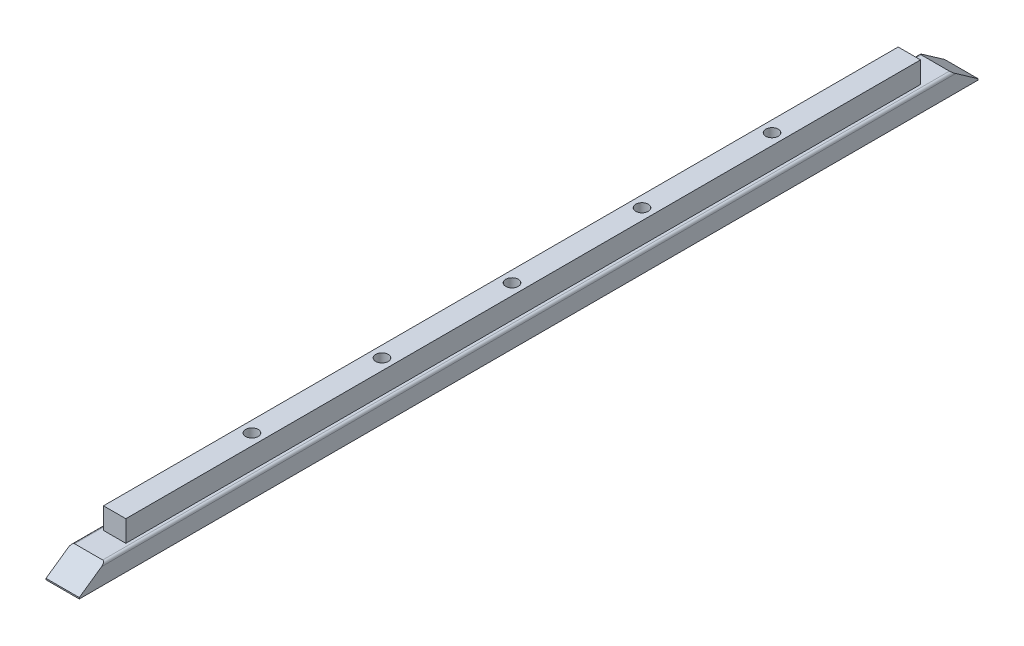
SolidWorks part; units mm, degrees
ref_plane "Front Plane" through (0, 0, 0) normal (0, 0, 1) x (1, 0, 0)
ref_plane "Top Plane" through (0, 0, 0) normal (0, 1, 0) x (1, 0, 0)
ref_plane "Right Plane" through (0, 0, 0) normal (1, 0, 0) x (0, 0, -1)
sketch "Sketch1" plane through (0, 0, 0) normal (0, 1, 0) x (1, 0, 0)
  line L0 (3.3, -162.8) -> (3.3, 10) construction
  line L5 (-3.2, -162.8) -> (3.2, -162.8)
  line L6 (-3.2, -162.8) -> (-3.2, 10)
  line L7 (-3.2, 10) -> (3.2, 10)
  line L8 (3.2, -162.8) -> (3.2, 10)
  line L9 (-3.3, 10) -> (-3.3, -162.8) construction
  line L11 (-3.3, -162.8) -> (3.3, -162.8) construction
  point P6 (0, 0)
  dimension "D1" = 0.1
  dimension "D2" = 0.1
  dimension "D3" = 10
extrude "Boss-Extrude1" add sketch "Sketch1" along normal offset from surface (3.75 mm away) 0.1
chamfer "Chamfer4" distance 5 angle 35 2 edges at (0, 3.75, 162.8) (0, 3.75, -10)
fillet "Fillet1" radius 0.5 2 edges at (-3.2, 3.75, 76.4) (3.2, 3.75, 76.4)
sketch "Sketch2" plane through (0, 3.75, 0) normal (0, 1, 0) x (1, 0, 0)
  line L0 (-2.25, -151.9548) -> (-2.25, -25.6452) construction
  line L1 (-2.15, 0) -> (2.15, 0)
  line L2 (-2.15, 0) -> (-2.15, -152.8)
  line L3 (-2.15, -152.8) -> (2.15, -152.8)
  line L4 (2.15, 0) -> (2.15, -152.8)
  line L6 (2.25, -156.6452) -> (2.25, -159.5) construction
  line L8 (-2.7, -157.8) -> (2.7, -157.8) construction
  line L9 (2.7, 5) -> (-2.7, 5) construction
  dimension "D1" = 0.1
  dimension "D2" = 0.1
  dimension "D3" = 5
  dimension "D4" = 5
extrude "Boss-Extrude2" add sketch "Sketch2" along normal offset from surface (4.1 mm away) 1
sketch "Sketch3" plane through (0, 0, 0) normal (0, -1, 0) x (1, 0, 0)
  line L0 (0, -10) -> (0, 162.8) construction
  line L1 (3.2, -10) -> (-3.2, -10) construction
  line L2 (-3.2, 162.8) -> (3.2, 162.8) construction
  point P8 (0, 76.4)
hole_wizard "CSK for M2 Flat Head Machine Screw1" positions "Sketch3" profile "Sketch4" countersink size "M2" standard "ANSI Metric" end condition through all
sketch "Sketch4" plane through (0, 0, 76.4) normal (1, 0, 0) x (0, 0, -1)
  line L0 (0, 0) -> (0, 7.85)
  line L1 (0, 7.85) -> (1.2, 7.85)
  line L2 (1.2, 7.85) -> (1.2, 1)
  line L3 (1.2, 1) -> (2.2, 0)
  line L5 (2.2, 0) -> (0, 0)
  line L6 (-1.2, 1) -> (-2.2, 0) construction
  line L11 (0, -6.35) -> (0, 107.95) construction
  dimension "Thru Hole Dia." = 2.4
  dimension "Thru Hole Depth" = 7.85
  dimension "Near C'Sink Dia." = 4.4
  dimension "Near C'Sink Angle" = 90
pattern_linear "LPattern1" count 3 spacing 25 along (0, 0, -1) count 3 spacing 25 along (0, 0, 1) of "CSK for M2 Flat Head Machine Screw1"
